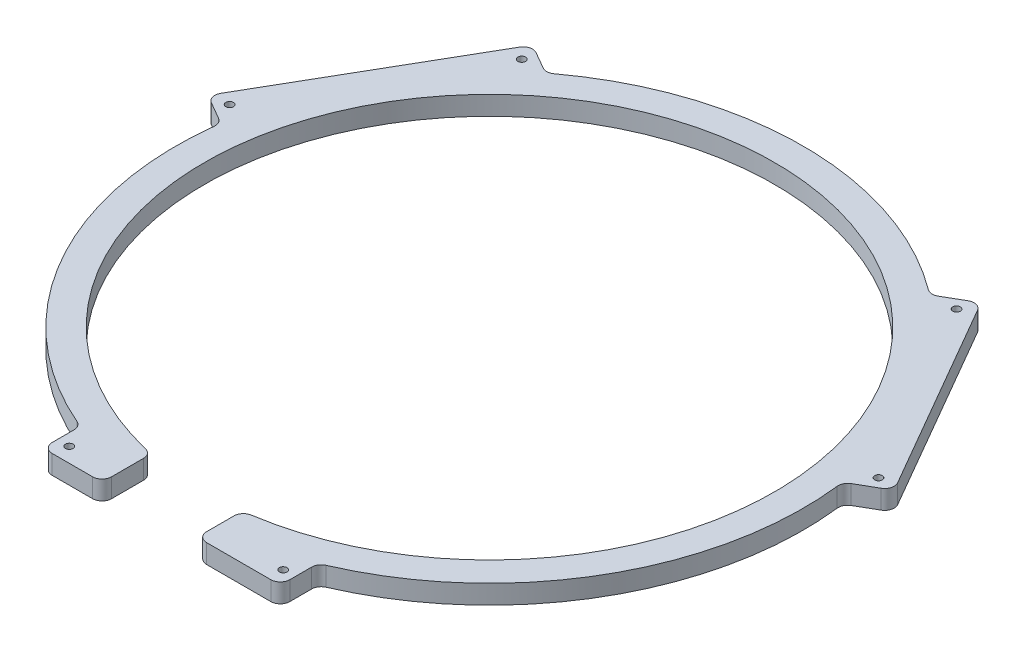
SolidWorks part; units mm, degrees
ref_plane "Front Plane" through (0, 0, 0) normal (0, 0, 1) x (1, 0, 0)
ref_plane "Top Plane" through (0, 0, 0) normal (0, 1, 0) x (1, 0, 0)
ref_plane "Right Plane" through (0, 0, 0) normal (1, 0, 0) x (0, 0, -1)
sketch "Sketch1" plane through (0, 0, 0) normal (0, 1, 0) x (1, 0, 0)
  line L0 (-75.0042, 160.8672) -> (-67.8302, 156.7253)
  line L1 (111.7737, 159.8634) -> (157.8164, 80.201)
  line L2 (106.3073, 161.324) -> (98.3653, 156.7288)
  line L3 (-125.0042, 74.2647) -> (-117.8302, 70.1228)
  line L4 (-126.4683, 79.7288) -> (-80.4683, 159.4031)
  line L5 (156.3533, 74.7353) -> (148.3642, 70.1228)
  line L6 (-30.7286, -87.0026) -> (-13.7286, -87.0026)
  line L7 (65.2714, -83.0026) -> (65.2714, -73.8039)
  line L8 (-34.7286, -83.0026) -> (-34.7286, -73.8077)
  line L10 (-9.7286, -83.0026) -> (-9.7286, -69.5481)
  line L12 (30.2714, -83.0026) -> (30.2714, -71.5209)
  line L13 (34.2714, -87.0026) -> (61.2714, -87.0026)
  arc A0 (67.683, -70.1328) -> (146.3908, 66.1985) centre (15.267, 51.0141) ccw
  circle A1 centre (-75.5988, 155.437) radius 1.6
  circle A2 centre (-120.5264, 77.4521) radius 1.6
  circle A3 centre (106.9093, 155.8853) radius 1.6
  circle A4 centre (151.9825, 77.9844) radius 1.6
  circle A5 centre (-29.7286, -80.8026) radius 1.6
  circle A6 centre (60.2714, -80.8026) radius 1.6
  arc A7 (93.9769, 156.9799) -> (-63.4449, 156.9784) centre (15.267, 51.0141) ccw
  arc A8 (-115.8567, 66.1985) -> (-37.1405, -70.1364) centre (15.267, 51.0141) ccw
  arc A9 (-117.8302, 70.1228) -> (-115.8567, 66.1985) centre (-119.8302, 66.6587) cw
  arc A10 (33.6583, -67.5682) -> (-12.7933, -65.659) centre (15.267, 51.0141) ccw
  arc A11 (-67.8302, 156.7253) -> (-63.4449, 156.9784) centre (-65.8302, 160.1894) ccw
  arc A12 (98.3653, 156.7288) -> (93.9769, 156.9799) centre (96.362, 160.191) cw
  arc A13 (148.3642, 70.1228) -> (146.3908, 66.1985) centre (150.3642, 66.6587) ccw
  arc A14 (65.2714, -73.8039) -> (67.683, -70.1328) centre (69.2714, -73.8039) cw
  arc A15 (-34.7286, -73.8077) -> (-37.1405, -70.1364) centre (-38.7286, -73.8077) ccw
  arc A16 (-13.7286, -87.0026) -> (-9.7286, -83.0026) centre (-13.7286, -83.0026) ccw
  arc A17 (34.2714, -87.0026) -> (30.2714, -83.0026) centre (34.2714, -83.0026) cw
  arc A18 (30.2714, -71.5209) -> (33.6583, -67.5682) centre (34.2714, -71.5209) cw
  arc A19 (-9.7286, -69.5481) -> (-12.7933, -65.659) centre (-13.7286, -69.5481) ccw
  arc A20 (-30.7286, -87.0026) -> (-34.7286, -83.0026) centre (-30.7286, -83.0026) cw
  arc A21 (61.2714, -87.0026) -> (65.2714, -83.0026) centre (61.2714, -83.0026) ccw
  arc A22 (157.8164, 80.201) -> (156.3533, 74.7353) centre (154.3533, 78.1994) cw
  arc A23 (111.7737, 159.8634) -> (106.3073, 161.324) centre (108.3105, 157.8618) ccw
  arc A24 (-125.0042, 74.2647) -> (-126.4683, 79.7288) centre (-123.0042, 77.7288) cw
  arc A25 (-75.0042, 160.8672) -> (-80.4683, 159.4031) centre (-77.0042, 157.4031) ccw
  point P27 (-115.53, 68.7947)
  point P30 (-65.53, 155.3973)
  point P37 (96.064, 155.3973)
  point P48 (30.2714, -87.0026)
  dimension "D1" = 4
extrude "Boss-Extrude2" add sketch "Sketch1" along normal blind 8
